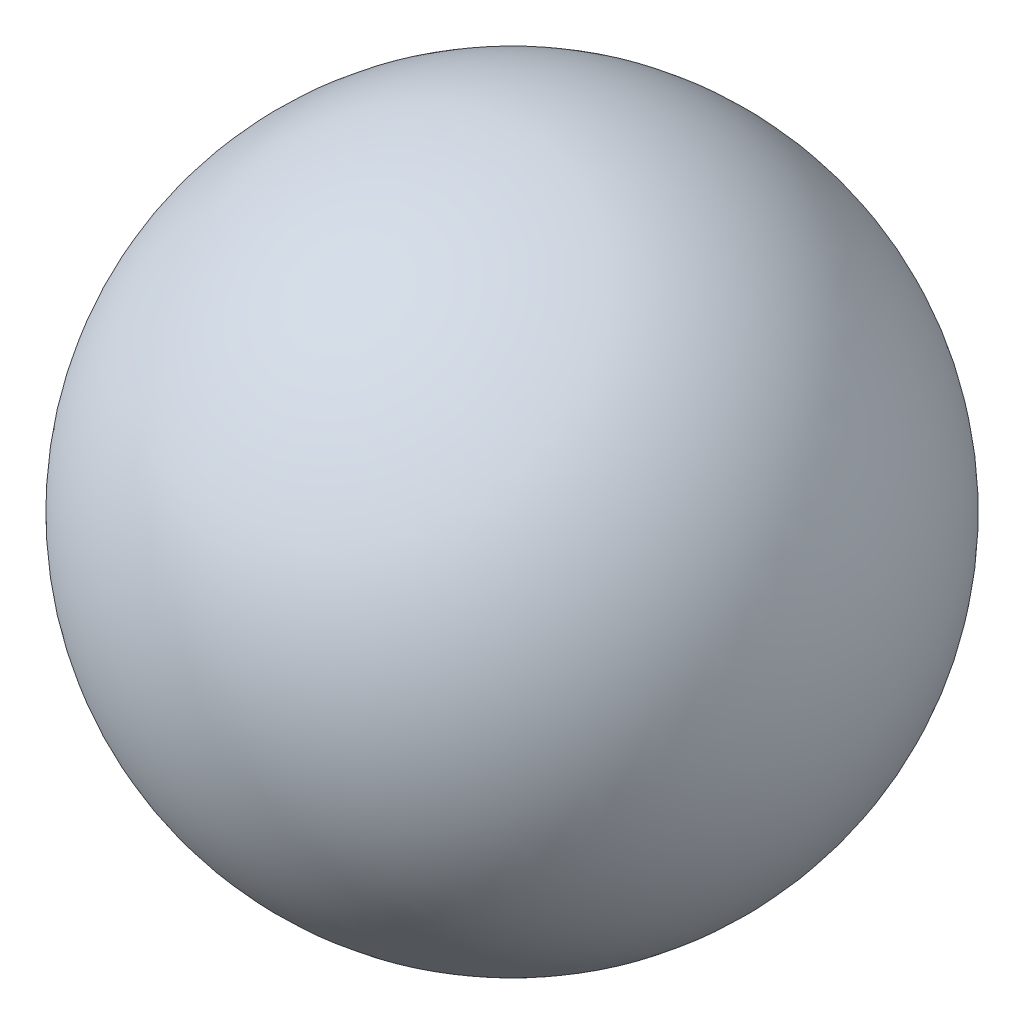
SolidWorks part; units mm, degrees
material "Golf ball"
ref_plane "Front Plane" through (0, 0, 0) normal (0, 0, 1) x (1, 0, 0)
ref_plane "Top Plane" through (0, 0, 0) normal (0, 1, 0) x (1, 0, 0)
ref_plane "Right Plane" through (0, 0, 0) normal (1, 0, 0) x (0, 0, -1)
sketch "Sketch1" plane through (0, 0, 0) normal (0, 0, 1) x (1, 0, 0)
  line L0 (0, -55) -> (0, 55) construction
  line L1 (0, -21.5) -> (0, 21.5)
  arc A0 (0, 21.5) -> (0, -21.5) centre (0, 0) cw
  point P9 (0, 0)
  dimension "D1" = 21.5
  dimension "D2" = 43
ref_axis "Axis1" through (0, 25.3, 0) along (0, -1, 0)
revolve "Revolve1" add sketch "Sketch1" angle 360 about axis through (0, 25.3, 0) along (0, -1, 0)
equation "\"D2@Sketch1\"=\"D1@Sketch1\"*2"
